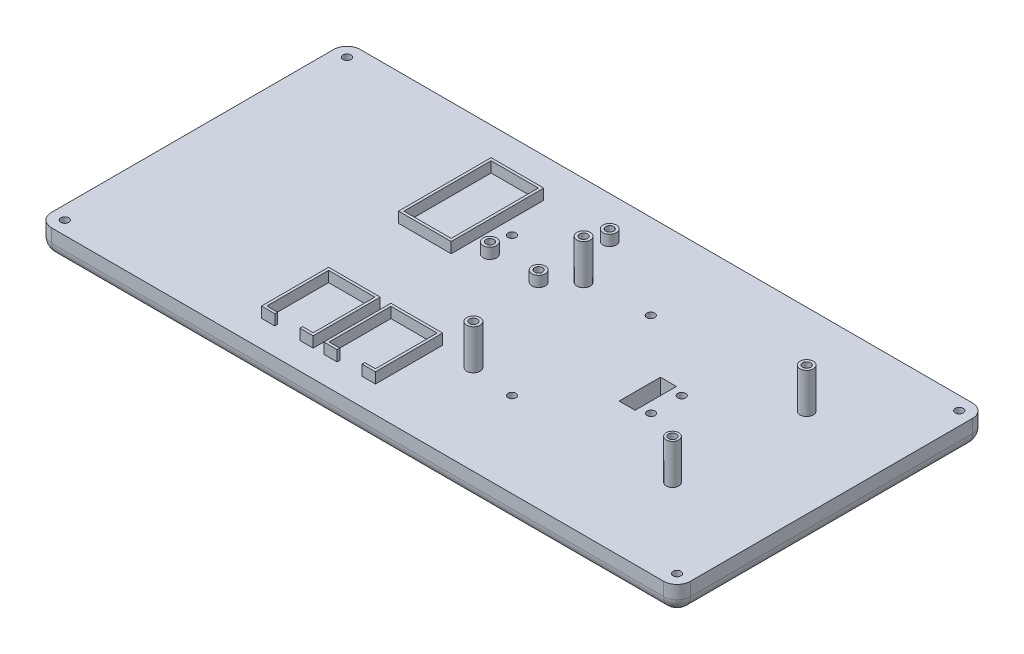
SolidWorks part; units mm, degrees
ref_plane "Front Plane" through (0, 0, 0) normal (0, 0, 1) x (1, 0, 0)
ref_plane "Top Plane" through (0, 0, 0) normal (0, 1, 0) x (1, 0, 0)
ref_plane "Right Plane" through (0, 0, 0) normal (1, 0, 0) x (0, 0, -1)
sketch "Sketch1" plane through (0, 0, 0) normal (0, 1, 0) x (1, 0, 0)
  line L1 (-120, 58) -> (120, 58)
  line L2 (-120, 58) -> (-120, -58)
  line L3 (-120, -58) -> (120, -58)
  line L4 (120, 58) -> (120, -58)
  line L5 (-120, 58) -> (120, -58) construction
  line L6 (-120, -58) -> (120, 58) construction
  point P0 (0, 0)
  dimension "D1" = 240
  dimension "D2" = 116
extrude "Boss-Extrude1" add sketch "Sketch1" along normal blind 10
sketch "Sketch2" plane through (0, 0, 0) normal (0, -1, 0) x (1, 0, 0)
  line L1 (-31.075, 31.075) -> (31.075, 31.075)
  line L2 (-31.075, 31.075) -> (-31.075, -31.075)
  line L3 (-31.075, -31.075) -> (31.075, -31.075)
  line L4 (31.075, 31.075) -> (31.075, -31.075)
  line L5 (-31.075, 31.075) -> (31.075, -31.075) construction
  line L6 (-31.075, -31.075) -> (31.075, 31.075) construction
  point P0 (0, 0)
  dimension "D1" = 62.15
  dimension "D2" = 62.15
extrude "Cut-Extrude1" cut sketch "Sketch2" against normal blind 2.5
sketch "Sketch3" plane through (0, 2.5, 0) normal (0, -1, 0) x (1, 0, 0)
  line L0 (0, 31.075) -> (0, -31.075) construction
  line L1 (31.075, 31.075) -> (-31.075, 31.075) construction
  line L2 (-31.075, -31.075) -> (31.075, -31.075) construction
  line L3 (-31.075, 0) -> (31.075, 0) construction
  line L4 (-31.075, 31.075) -> (-31.075, -31.075) construction
  line L5 (31.075, -31.075) -> (31.075, 31.075) construction
  line L6 (31.075, 31.075) -> (-31.075, 31.075) construction
  line L7 (-31.075, 31.075) -> (-31.075, -31.075) construction
  circle A0 centre (-26.075, 26.075) radius 1.5
  circle A1 centre (-26.075, -26.075) radius 1.5
  circle A2 centre (26.075, -26.075) radius 1.5
  circle A3 centre (26.075, 26.075) radius 1.5
  dimension "D1" = 3
  dimension "D3" = 5
  dimension "D2" = 5
extrude "Cut-Extrude2" cut sketch "Sketch3" against normal up to next
sketch "Sketch4" plane through (0, 0, 0) normal (0, -1, 0) x (1, 0, 0)
  line L0 (120, 58) -> (120, -58) construction
  line L1 (48, 7.75) -> (60, 7.75)
  line L2 (48, 7.75) -> (48, -7.75)
  line L3 (48, -7.75) -> (60, -7.75)
  line L4 (60, 7.75) -> (60, -7.75)
  line L5 (48, 7.75) -> (60, -7.75) construction
  line L6 (48, -7.75) -> (60, 7.75) construction
  point P0 (54, 0)
  dimension "D1" = 12
  dimension "D2" = 15.5
  dimension "D3" = 60
extrude "Cut-Extrude3" cut sketch "Sketch4" against normal blind 2.5
sketch "Sketch6" plane through (0, 2.5, 0) normal (0, -1, 0) x (1, 0, 0)
  line L0 (60, -7.75) -> (60, 7.75) construction
  line L1 (60, 7.75) -> (48, 7.75) construction
  line L2 (48, -7.75) -> (60, -7.75) construction
  circle A0 centre (58, 5.75) radius 1.5
  circle A1 centre (58, -5.75) radius 1.5
  dimension "D1" = 3
  dimension "D2" = 3
  dimension "D3" = 2
  dimension "D4" = 2
  dimension "D5" = 2
  dimension "D6" = 2
extrude "Cut-Extrude4" cut sketch "Sketch6" against normal up to next and the other way through all
sketch "Sketch7" plane through (0, 2.5, 0) normal (0, -1, 0) x (1, 0, 0)
  line L0 (48, -7.75) -> (60, -7.75) construction
  line L1 (48, 7.75) -> (54, 7.75)
  line L2 (48, 7.75) -> (48, -7.75)
  line L3 (48, -7.75) -> (54, -7.75)
  line L4 (54, 7.75) -> (54, -7.75)
extrude "Cut-Extrude5" cut sketch "Sketch7" against normal up to next
sketch "Sketch8" plane through (0, 10, 0) normal (0, 1, 0) x (1, 0, 0)
  line L1 (1.2, 26.7) -> (100, 26.7) construction
  line L2 (1.2, 26.7) -> (1.2, -26.7) construction
  line L3 (1.2, -26.7) -> (100, -26.7) construction
  line L4 (100, 26.7) -> (100, -26.7) construction
  line L5 (1.2, 26.7) -> (100, -26.7) construction
  line L6 (1.2, -26.7) -> (100, 26.7) construction
  line L11 (120, -58) -> (120, 58) construction
  line L15 (-120, -58) -> (120, -58) construction
  circle A0 centre (2.7, 24.2) radius 1.5
  circle A1 centre (9.7, -24.2) radius 1.5
  circle A2 centre (86.5, 24.2) radius 1.5
  circle A3 centre (84.5, -24.2) radius 1.5
  circle A4 centre (86.5, 24.2) radius 2.5
  circle A5 centre (84.5, -24.2) radius 2.3473
  circle A6 centre (9.7, -24.2) radius 2.5
  circle A7 centre (2.7, 24.2) radius 2.5
  point P0 (50.6, 0)
  dimension "D7" = 3
  dimension "D8" = 3
  dimension "D9" = 3
  dimension "D10" = 3
  dimension "D11" = 2.5
  dimension "D13" = 8.5
  dimension "D14" = 2.5
  dimension "D12" = 15.5
  dimension "D16" = 13.5
  dimension "D17" = 2.5
  dimension "D18" = 5
  dimension "D19" = 5
  dimension "D20" = 5
  dimension "D1" = 98.8
  dimension "D2" = 53.4
  dimension "D3" = 20
  dimension "D4" = 58
  dimension "D15" = 2.5
extrude "Boss-Extrude2" add sketch "Sketch8" along normal blind 15
sketch "Sketch9" plane through (0, 10, 0) normal (0, 1, 0) x (1, 0, 0)
  line L0 (-0.3, 58) -> (-0.3, -58) construction
  line L1 (-25.6, 47) -> (-4.3, 47) construction
  line L2 (-25.6, 47) -> (-25.6, 8.5) construction
  line L3 (-25.6, 8.5) -> (-4.3, 8.5) construction
  line L4 (-4.3, 47) -> (-4.3, 8.5) construction
  line L5 (-25.6, 47) -> (-4.3, 8.5) construction
  line L6 (-25.6, 8.5) -> (-4.3, 47) construction
  line L7 (-53.1, 47) -> (-29.6, 47) construction
  line L8 (-53.1, 47) -> (-53.1, 5) construction
  line L9 (-53.1, 5) -> (-29.6, 5) construction
  line L10 (-29.6, 47) -> (-29.6, 5) construction
  line L11 (-53.1, 47) -> (-29.6, 5) construction
  line L12 (-53.1, 5) -> (-29.6, 47) construction
  line L13 (120, 58) -> (-120, 58) construction
  line L14 (-120, -58) -> (120, -58) construction
  line L15 (-76.2, -9.5) -> (-54.9, -9.5) construction
  line L16 (-103.7, -9) -> (-80.2, -9) construction
  line L17 (-17.7, -47) -> (-17.7, -48)
  line L18 (-21.7, -23.8) -> (-4.3, -23.8)
  line L19 (-21.7, -23.8) -> (-21.7, -47)
  line L20 (-21.7, -47) -> (-17.7, -47)
  line L21 (-4.3, -23.8) -> (-4.3, -47)
  line L22 (-21.7, -23.8) -> (-4.3, -47) construction
  line L23 (-21.7, -47) -> (-4.3, -23.8) construction
  line L24 (-22.7, -22.8) -> (-3.3, -22.8)
  line L25 (-22.7, -22.8) -> (-22.7, -48)
  line L26 (-22.7, -48) -> (-17.7, -48)
  line L27 (-3.3, -22.8) -> (-3.3, -48)
  line L28 (-22.7, -22.8) -> (-3.3, -48) construction
  line L29 (-22.7, -48) -> (-3.3, -22.8) construction
  line L30 (-8.3, -47) -> (-8.3, -48)
  line L31 (-8.3, -47) -> (-4.3, -47)
  line L32 (-8.3, -48) -> (-3.3, -48)
  line L33 (-24.7, -58) -> (-24.7, -13.4898) construction
  line L34 (-26.7, -48) -> (-46.1, -22.8) construction
  line L35 (-26.7, -22.8) -> (-46.1, -48) construction
  line L36 (-27.7, -47) -> (-45.1, -23.8) construction
  line L37 (-27.7, -23.8) -> (-45.1, -47) construction
  line L38 (-41.1, -48) -> (-46.1, -48)
  line L39 (-41.1, -47) -> (-45.1, -47)
  line L40 (-41.1, -47) -> (-41.1, -48)
  line L41 (-46.1, -22.8) -> (-46.1, -48)
  line L42 (-26.7, -48) -> (-31.7, -48)
  line L43 (-26.7, -22.8) -> (-26.7, -48)
  line L44 (-26.7, -22.8) -> (-46.1, -22.8)
  line L45 (-45.1, -23.8) -> (-45.1, -47)
  line L46 (-27.7, -47) -> (-31.7, -47)
  line L47 (-27.7, -23.8) -> (-27.7, -47)
  line L48 (-27.7, -23.8) -> (-45.1, -23.8)
  line L49 (-31.7, -47) -> (-31.7, -48)
  line L50 (-48.1, -58) -> (-48.1, -12.5562) construction
  line L51 (-31.46, 43.383) -> (-31.46, 8.617)
  line L52 (-50.24, 42.383) -> (-32.46, 42.383)
  line L53 (-50.24, 42.383) -> (-50.24, 9.617)
  line L54 (-50.24, 9.617) -> (-32.46, 9.617)
  line L67 (31.45, 58) -> (31.45, -58) construction
  line L102 (-32.46, 42.383) -> (-32.46, 9.617)
  line L103 (-50.24, 42.383) -> (-32.46, 9.617) construction
  line L104 (-50.24, 9.617) -> (-32.46, 42.383) construction
  line L105 (-51.24, 8.617) -> (-31.46, 8.617)
  line L106 (-51.24, 43.383) -> (-51.24, 8.617)
  line L107 (-51.24, 43.383) -> (-31.46, 43.383)
  circle A0 centre (2.7, 24.2) radius 1.5 construction
  circle A1 centre (-5.8, 42.5) radius 1.5
  circle A2 centre (-5.8, 15.8) radius 1.5
  circle A3 centre (-24.1, 15.8) radius 1.5
  circle A4 centre (-24.1, 15.8) radius 2.5
  circle A5 centre (-5.8, 15.8) radius 2.5
  circle A6 centre (-5.8, 42.5) radius 2.5
  circle A7 centre (-50.6, 44.5) radius 1.5 construction
  circle A8 centre (-32.1, 44.5) radius 1.5 construction
  circle A9 centre (-32.1, 7.5) radius 1.5 construction
  circle A10 centre (-50.6, 7.5) radius 1.5 construction
  circle A11 centre (-50.6, 7.5) radius 2.5 construction
  circle A12 centre (-32.1, 7.5) radius 2.5 construction
  circle A13 centre (-32.1, 44.5) radius 2.5 construction
  circle A14 centre (-50.6, 44.5) radius 2.5 construction
  point P0 (-14.95, 27.75)
  point P5 (-41.35, 26)
  point P20 (-13, -35.4)
  point P27 (-13, -35.4)
  point P50 (-36.4, -35.4)
  point P53 (-41.35, 26)
  dimension "D23" = 3
  dimension "D24" = 3
  dimension "D25" = 3
  dimension "D28" = 5
  dimension "D29" = 5
  dimension "D30" = 5
  dimension "D31" = 3
  dimension "D32" = 3
  dimension "D33" = 3
  dimension "D34" = 3
  dimension "D43" = 5
  dimension "D44" = 5
  dimension "D45" = 5
  dimension "D46" = 5
  dimension "D1" = 38.5
  dimension "D2" = 21.3
  dimension "D3" = 3
  dimension "D4" = 4
  dimension "D5" = 18
  dimension "D6" = 42
  dimension "D7" = 23.5
  dimension "D8" = 4
  dimension "D9" = 11
  dimension "D10" = 14
  dimension "D11" = 17.4
  dimension "D12" = 23.2
  dimension "D13" = 11
  dimension "D14" = 4
  dimension "D15" = 25.2
  dimension "D16" = 19.4
  dimension "D17" = 4
  dimension "D18" = 4
  dimension "D19" = 2
  dimension "D20" = 2
  dimension "D22" = 4.5
  dimension "D26" = 7.3
  dimension "D27" = 7.3
  dimension "D35" = 2.5
  dimension "D36" = 2.5
  dimension "D37" = 2.5
  dimension "D38" = 2.5
  dimension "D39" = 2.5
  dimension "D40" = 2.5
  dimension "D41" = 2.5
  dimension "D42" = 2.5
  dimension "D47" = 32.766
  dimension "D48" = 17.78
  dimension "D49" = 1
extrude "Boss-Extrude3" add sketch "Sketch9" along normal blind 4
sketch "Sketch10" plane through (0, 10, 0) normal (0, 1, 0) x (1, 0, 0)
  line L0 (-112, 50) -> (112, 50)
  line L1 (-120, 58) -> (120, 58)
  line L2 (-120, 58) -> (-120, -58)
  line L3 (-120, -58) -> (120, -58)
  line L4 (120, 58) -> (120, -58)
  line L5 (-120, 58) -> (120, -58) construction
  line L6 (-120, -58) -> (120, 58) construction
  line L7 (112, 50) -> (112, -50)
  line L8 (-112, -50) -> (112, -50)
  line L9 (-112, 50) -> (-112, -50)
  point P0 (0, 0)
  dimension "D1" = 8
extrude "Boss-Extrude4" [suppressed] add sketch "Sketch10" along normal blind 80
sketch "Sketch11" [suppressed] plane through (112, 0, 0) normal (-1, 0, 0) x (0, 0, 1)
  line L0 (-50, 90) -> (-50, 10) construction
  line L1 (-37, 82.5) -> (23, 82.5) construction
  line L2 (-37, 82.5) -> (-37, 17.5) construction
  line L3 (-37, 17.5) -> (23, 17.5) construction
  line L4 (23, 82.5) -> (23, 17.5) construction
  line L5 (-37, 82.5) -> (23, 17.5) construction
  line L6 (-37, 17.5) -> (23, 82.5) construction
  line L7 (-27.9, 70.9) -> (13.9, 70.9) construction
  line L8 (-27.9, 70.9) -> (-27.9, 29.1) construction
  line L9 (-27.9, 29.1) -> (13.9, 29.1) construction
  line L10 (13.9, 70.9) -> (13.9, 29.1) construction
  line L11 (-27.9, 70.9) -> (13.9, 29.1) construction
  line L12 (-27.9, 29.1) -> (13.9, 70.9) construction
  line L15 (50, 90) -> (-50, 90) construction
  circle A0 centre (-22.9, 65.9) radius 1.5
  circle A1 centre (8.9, 65.9) radius 1.5
  circle A2 centre (8.9, 34.1) radius 1.5
  circle A3 centre (-22.9, 34.1) radius 1.5
  circle A4 centre (-7, 67.5) radius 4.5
  point P0 (-7, 50)
  point P6 (-7, 50)
  dimension "D5" = 3
  dimension "D6" = 3
  dimension "D8" = 3
  dimension "D7" = 3
  dimension "D19" = 9
  dimension "D1" = 65
  dimension "D2" = 60
  dimension "D3" = 41.8
  dimension "D4" = 41.8
  dimension "D10" = 5
  dimension "D11" = 5
  dimension "D12" = 5
  dimension "D13" = 5
  dimension "D14" = 5
  dimension "D15" = 5
  dimension "D16" = 5
  dimension "D17" = 43
  dimension "D18" = 40
  dimension "D20" = 15
  dimension "D21" = 30
  dimension "D9" = 5
extrude "Cut-Extrude6" [suppressed] cut sketch "Sketch11" against normal up to next contours A1 | A3 | A2 | A0
sketch "Sketch13" [suppressed] plane through (120, 0, 0) normal (1, 0, 0) x (0, 0, -1)
  circle A0 centre (-8.9, 65.9) radius 3
  circle A1 centre (22.9, 65.9) radius 3
  circle A2 centre (22.9, 34.1) radius 3
  circle A3 centre (-8.9, 34.1) radius 3
  dimension "D1" = 6
  dimension "D2" = 6
  dimension "D3" = 6
  dimension "D4" = 6
extrude "Cut-Extrude7" [suppressed] cut sketch "Sketch13" against normal blind 4
sketch "Sketch24" [suppressed] plane through (-112, 0, 0) normal (1, 0, 0) x (0, 0, -1)
  line L0 (50, 10) -> (-50, 10) construction
  line L1 (-43, 34) -> (43, 34) construction
  line L2 (-43, 34) -> (-43, 75) construction
  line L3 (-43, 75) -> (43, 75) construction
  line L4 (43, 34) -> (43, 75) construction
  line L5 (-43, 34) -> (43, 75) construction
  line L6 (-43, 75) -> (43, 34) construction
  line L7 (50, 90) -> (-50, 90) construction
  line L8 (0, 75) -> (0, 34) construction
  circle A0 centre (-38, 70) radius 1.5
  circle A1 centre (-38, 39) radius 1.5
  circle A2 centre (38, 39) radius 1.5
  circle A3 centre (38, 70) radius 1.5
  point P0 (0, 54.5)
  point P9 (0, 10)
  dimension "D4" = 3
  dimension "D5" = 3
  dimension "D6" = 5
  dimension "D7" = 5
  dimension "D8" = 5
  dimension "D9" = 5
  dimension "D1" = 86
  dimension "D2" = 41
  dimension "D3" = 15
extrude "Cut-Extrude14" [suppressed] cut sketch "Sketch24" against normal up to next
sketch "Sketch14" [suppressed] plane through (-112, 0, 0) normal (1, 0, 0) x (0, 0, -1)
  circle A0 centre (0, 54.5) radius 13
  circle A2 centre (0, 54.5) radius 11
  dimension "D1" = 26
  dimension "D2" = 22
  dimension "D3" = 0
extrude "Boss-Extrude6" [suppressed] add sketch "Sketch14" along normal blind 8
sketch "Sketch16" [suppressed] plane through (-112, 0, 0) normal (1, 0, 0) x (0, 0, -1)
  circle A0 centre (0, 54.5) radius 10.5
  circle A1 centre (0, 54.5) radius 11
  dimension "D1" = 21
  dimension "D2" = 22
extrude "Boss-Extrude7" [suppressed] add sketch "Sketch16" along normal blind 1
sketch "Sketch18" [suppressed] plane through (0, 0, -50) normal (0, 0, 1) x (1, 0, 0)
  line L0 (-60.25, 80) -> (-60.25, 38) construction
  line L1 (-72, 80) -> (-48.5, 80) construction
  line L2 (-72, 80) -> (-72, 38) construction
  line L3 (-72, 38) -> (-48.5, 38) construction
  line L4 (-48.5, 80) -> (-48.5, 38) construction
  line L5 (-72, 80) -> (-48.5, 38) construction
  line L6 (-72, 38) -> (-48.5, 80) construction
  line L7 (-72, 59.4256) -> (-48.5, 59.4256) construction
  line L8 (112, 90) -> (-112, 90) construction
  line L9 (-112, 90) -> (-112, 10) construction
  circle A0 centre (-69.5, 77.5) radius 1.5
  circle A1 centre (-69.5, 77.5) radius 2.5
  circle A2 centre (-69.5, 41.3512) radius 1.5
  circle A3 centre (-69.5, 41.3512) radius 2.5
  circle A4 centre (-51, 41.3512) radius 2.5
  circle A5 centre (-51, 41.3512) radius 1.5
  circle A6 centre (-51, 77.5) radius 2.5
  circle A7 centre (-51, 77.5) radius 1.5
  point P0 (-60.25, 59)
  dimension "D3" = 3
  dimension "D4" = 5
  dimension "D5" = 2.5
  dimension "D6" = 2.5
  dimension "D1" = 42
  dimension "D2" = 23.5
  dimension "D7" = 10
  dimension "D8" = 40
sketch "Sketch17" [suppressed] plane through (-112, 0, 0) normal (1, 0, 0) x (0, 0, -1)
  circle A0 centre (0, 54.5) radius 4.5
  dimension "D1" = 9
extrude "Cut-Extrude9" [suppressed] cut sketch "Sketch17" against normal up to next
extrude "Boss-Extrude8" [suppressed] add sketch "Sketch18" along normal blind 4
fillet "Fillet1" radius 5 8 edges at (120, 5, -58) (-120, 5, -58) (0, 0, -58) (-120, 0, 0) (0, 0, 58) (-120, 5, 58) (120, 0, 0) (120, 5, 58)
sketch "Sketch19" [suppressed] plane through (0, 90, 0) normal (0, 1, 0) x (1, 0, 0)
  circle A3 centre (115, 53) radius 1.5
  circle A4 centre (-115, 53) radius 1.5
  circle A5 centre (-115, -53) radius 1.5
  circle A6 centre (115, -53) radius 1.5
  dimension "D1" = 3
  dimension "D2" = 3
  dimension "D3" = 3
  dimension "D4" = 3
extrude "Cut-Extrude10" [suppressed] cut sketch "Sketch19" against normal blind 20
sketch "Sketch20" [suppressed] plane through (120, 0, 0) normal (1, 0, 0) x (0, 0, -1)
  line L0 (0, 90) -> (0, 0) construction
  line L1 (-53, 90) -> (53, 90) construction
  circle A0 centre (-23, 82) radius 2
  circle A1 centre (23, 82) radius 2
  dimension "D1" = 23
  dimension "D2" = 4
  dimension "D3" = 8
extrude "Cut-Extrude11" [suppressed] cut sketch "Sketch20" against normal up to next
sketch "Sketch21" [suppressed] plane through (112, 0, 0) normal (-1, 0, 0) x (0, 0, 1)
  line L1 (-26, 87) -> (-20, 87)
  line L2 (-26, 87) -> (-26, 77)
  line L3 (-26, 77) -> (-20, 77)
  line L4 (-20, 87) -> (-20, 77)
  line L5 (-26, 87) -> (-20, 77) construction
  line L6 (-26, 77) -> (-20, 87) construction
  line L7 (20, 87) -> (26, 87)
  line L8 (20, 87) -> (20, 77)
  line L9 (20, 77) -> (26, 77)
  line L10 (26, 87) -> (26, 77)
  line L11 (20, 87) -> (26, 77) construction
  line L12 (20, 77) -> (26, 87) construction
  circle A0 centre (23, 82) radius 2
  circle A1 centre (-23, 82) radius 2
  point P0 (-23, 82)
  point P6 (23, 82)
  dimension "D5" = 4
  dimension "D6" = 4
  dimension "D1" = 6
  dimension "D2" = 6
  dimension "D3" = 10
  dimension "D4" = 10
extrude "Boss-Extrude9" [suppressed] add sketch "Sketch21" along normal blind 13
sketch "Sketch22" [suppressed] plane through (0, 87, 0) normal (0, 1, 0) x (1, 0, 0)
  line L0 (99, -26) -> (99, -20) construction
  line L1 (99, -20) -> (112, -20) construction
  line L2 (99, 20) -> (99, 26) construction
  line L3 (99, 26) -> (112, 26) construction
  circle A0 centre (105.5, -23) radius 1.5
  circle A1 centre (105.5, 23) radius 1.5
  dimension "D1" = 3
  dimension "D2" = 6.5
  dimension "D3" = 3
  dimension "D4" = 3
  dimension "D5" = 6.5
  dimension "D6" = 3
extrude "Cut-Extrude12" [suppressed] cut sketch "Sketch22" against normal up to next
sketch "Sketch23" [suppressed] plane through (120, 0, 0) normal (1, 0, 0) x (0, 0, -1)
  line L0 (0, 90) -> (0, 5) construction
  line L1 (-53, 90) -> (53, 90) construction
  line L2 (-53, 5) -> (53, 5) construction
  line L3 (-9.0972, 80) -> (9.0972, 80) construction
  circle A0 centre (5, 78) radius 1
  circle A1 centre (-5, 78) radius 1
  circle A2 centre (5, 74) radius 1
  circle A3 centre (-5, 74) radius 1
  circle A4 centre (-5, 86) radius 1
  circle A5 centre (5, 86) radius 1
  circle A6 centre (-5, 82) radius 1
  circle A7 centre (5, 82) radius 1
  circle A8 centre (0, 80) radius 3
  point P24 (0, 80)
  dimension "D1" = 2
  dimension "D2" = 2
  dimension "D3" = 5
  dimension "D4" = 5
  dimension "D5" = 12
  dimension "D6" = 12
  dimension "D7" = 2
  dimension "D8" = 2
  dimension "D9" = 5
  dimension "D10" = 5
  dimension "D11" = 4
  dimension "D12" = 4
  dimension "D13" = 2
  dimension "D14" = 6
extrude "Cut-Extrude13" [suppressed] cut sketch "Sketch23" against normal up to next
sketch "Sketch25" plane through (0, 10, 0) normal (0, 1, 0) x (1, 0, 0)
  circle A0 centre (-115, 53) radius 1.5
  circle A1 centre (-115, -53) radius 1.5
  circle A2 centre (115, -53) radius 1.5
  circle A3 centre (115, 53) radius 1.5
  dimension "D1" = 3
  dimension "D2" = 3
  dimension "D3" = 3
  dimension "D4" = 3
extrude "Cut-Extrude15" cut sketch "Sketch25" against normal up to next
equation "\"D2@Sketch2\"=\"D1@Sketch2\""
equation "\"D15@Sketch9\"=\"D12@Sketch9\"+2"
equation "\"D16@Sketch9\"=\"D11@Sketch9\"+2"
equation "\"D17@Sketch11\"=86/2"
equation "\"D18@Sketch11\"=80/2"
